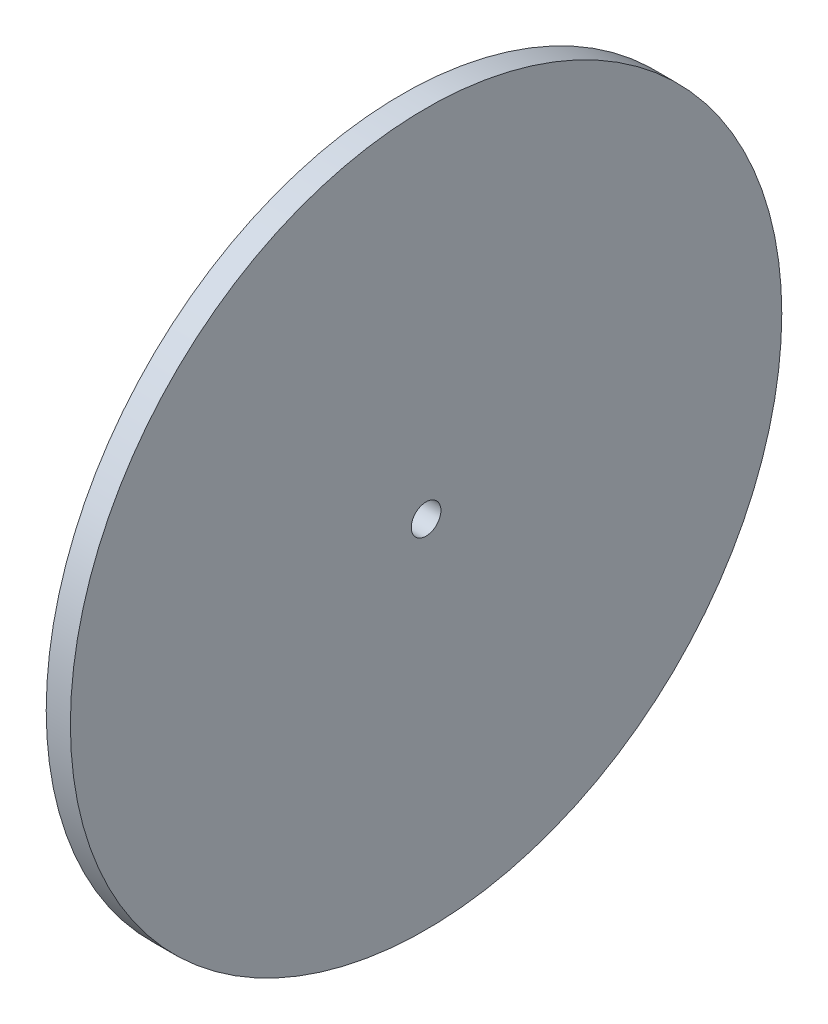
SolidWorks part; units mm, degrees
ref_plane "Front Plane" through (0, 0, 0) normal (0, 0, 1) x (1, 0, 0)
ref_plane "Top Plane" through (0, 0, 0) normal (0, 1, 0) x (1, 0, 0)
ref_plane "Right Plane" through (0, 0, 0) normal (1, 0, 0) x (0, 0, -1)
sketch "Sketch2" plane through (0, 0, 0) normal (0, 0, 1) x (1, 0, 0)
  line L0 (0, 0) -> (0, 24)
  line L1 (0, 24) -> (-1.63, 24)
  line L2 (-1.63, 24) -> (-1.63, 3.5)
  line L3 (-1.63, 3.5) -> (-3.79, 3.5)
  line L4 (-3.79, 3.5) -> (-3.79, 2.35)
  line L5 (-3.79, 2.35) -> (-1.63, 2.35)
  line L6 (-1.63, 2.35) -> (-1.63, 0)
  line L7 (-1.63, 0) -> (0, 0)
  dimension "D1" = 24
  dimension "D2" = 3.5
  dimension "D3" = 1.15
  dimension "D4" = 2.16
  dimension "D5" = 1.63
  dimension "D6" = 1.63
revolve "Revolve1" add sketch "Sketch2" angle 360 about L7
sketch "Sketch3" plane through (0, 0, 0) normal (1, 0, 0) x (0, 0, -1)
  circle A0 centre (0, 0) radius 1
  dimension "D1" = 2
extrude "Cut-Extrude1" cut sketch "Sketch3" against normal through all
